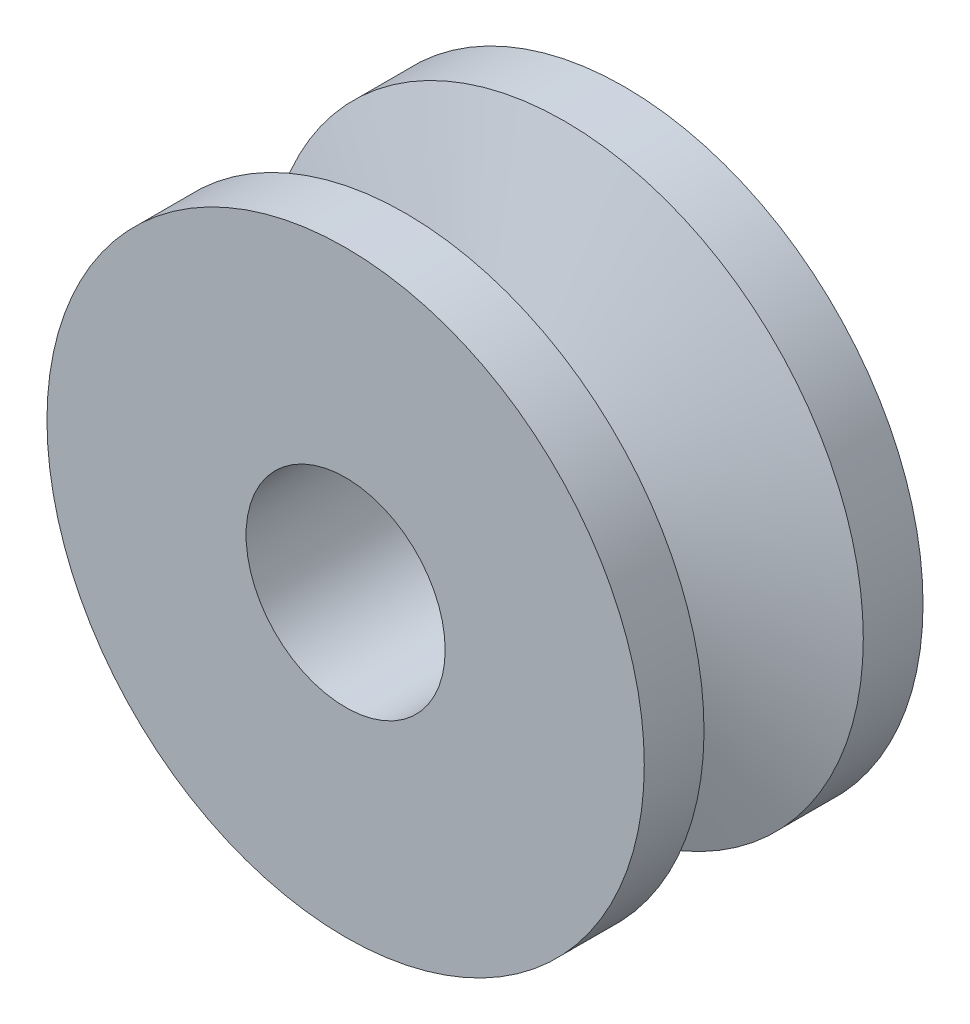
SolidWorks part; units mm, degrees
ref_plane "Front Plane" through (0, 0, 0) normal (0, 0, 1) x (1, 0, 0)
ref_plane "Top Plane" through (0, 0, 0) normal (0, 1, 0) x (1, 0, 0)
ref_plane "Right Plane" through (0, 0, 0) normal (1, 0, 0) x (0, 0, -1)
sketch "Sketch1" plane through (0, 0, 0) normal (0, 0, 1) x (1, 0, 0)
  circle A0 centre (0, 0) radius 7.5
  circle A1 centre (0, 0) radius 2.5
  dimension "D1" = 5
  dimension "D2" = 15
extrude "Boss-Extrude1" add sketch "Sketch1" along normal blind 7
sketch "Sketch2" plane through (0, 0, 0) normal (0, 1, 0) x (1, 0, 0)
  line L0 (3, -4) -> (3, -3)
  line L1 (0, 0) -> (0, -9.1683) construction
  line L4 (7.5, -7) -> (7.5, 0) construction
  line L7 (7.5, -5.5) -> (7.5, -1.5)
  line L8 (3, -4) -> (7.5, -5.5)
  line L9 (3, -3) -> (7.5, -1.5)
  point P12 (3, -3.5)
  dimension "D1" = 3
  dimension "D2" = 1.5
  dimension "D3" = 1.5
  dimension "D4" = 1
  dimension "D5" = 3.5
revolve "Cut-Revolve1" cut sketch "Sketch2" angle 360 about L1
sketch "Sketch3" plane through (0, 0, 0) normal (0, 0, 1) x (1, 0, 0)
  line L0 (-0.7681, -2.9) -> (0.7681, -2.9)
  circle A0 centre (0, 0) radius 3 construction
  arc A1 (-0.7681, -2.9) -> (0.7681, -2.9) centre (0, 0) ccw
  point P1 (0, -3)
  dimension "D1" = 0.1
extrude "Cut-Extrude2" cut sketch "Sketch3" along normal up to surface (4 mm away)
